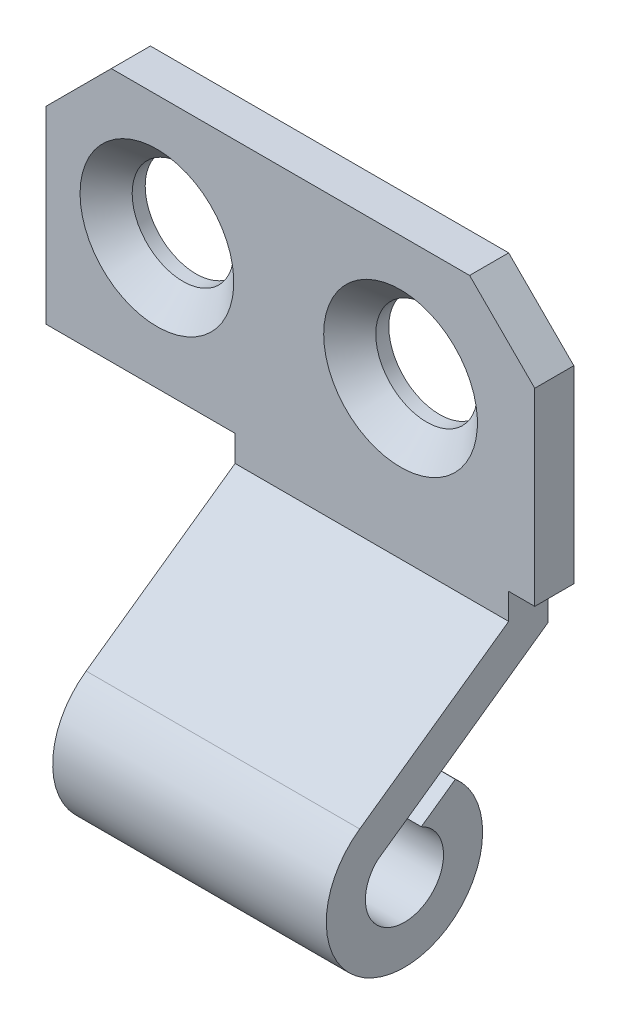
SolidWorks part; units mm, degrees
ref_plane "Płaszczyzna przednia" through (0, 0, 0) normal (0, 0, 1) x (1, 0, 0)
ref_plane "Płaszczyzna górna" through (0, 0, 0) normal (0, 1, 0) x (1, 0, 0)
ref_plane "Płaszczyzna prawa" through (0, 0, 0) normal (1, 0, 0) x (0, 0, -1)
sketch "Szkic1" plane through (0, 0, 0) normal (0, 0, 1) x (1, 0, 0)
  line L0 (-13.75, 9.75) -> (-18.75, 4.75)
  line L1 (-13.75, 9.75) -> (13.75, 9.75)
  line L2 (-18.75, 4.75) -> (-18.75, -9.75)
  line L3 (-18.75, -9.75) -> (-4.25, -9.75)
  line L4 (18.75, 4.75) -> (18.75, -9.75)
  line L5 (-4.25, -9.75) -> (-4.25, -11.75)
  line L6 (13.75, 9.75) -> (18.75, 4.75)
  line L7 (16.75, -9.75) -> (16.75, -11.75)
  line L8 (-4.25, -11.75) -> (16.75, -11.75)
  line L9 (16.75, -9.75) -> (18.75, -9.75)
  circle A0 centre (8.45, 0.25) radius 3.9
  circle A1 centre (-10.25, 0.25) radius 3.9
  dimension "D7" = 7.8
  dimension "D1" = 135
  dimension "D2" = 14.5
  dimension "D3" = 18.75
  dimension "D4" = 9.75
  dimension "D5" = 37.5
  dimension "D6" = 5
  dimension "D8" = 10.3
  dimension "D9" = 9.5
  dimension "D10" = 8.5
  dimension "D12" = 2
  dimension "D13" = 2
  dimension "D11" = 21
extrude "Dodanie-wyciągnięcie1" add sketch "Szkic1" along normal blind 3
chamfer "Sfazowanie1" distance 2 angle 45 2 edges at (-6.35, 0.25, 3) (12.35, 0.25, 3)
sketch "Szkic2" plane through (0, 0, 0) normal (1, 0, 0) x (0, 0, -1)
  line L0 (-3, -11.75) -> (-14.4334, -19.8295)
  line L1 (0, -13.3486) -> (0, -11.75)
  line L2 (0, -11.75) -> (-3, -11.75)
  line L3 (0, -13.3486) -> (-13.0935, -22.6012)
  line L10 (-7.0922, -20.1971) -> (-9.7054, -22.0437)
  arc A0 (-14.4334, -19.8295) -> (-7.0922, -20.1971) centre (-11, -24.75) ccw
  arc A1 (-13.0935, -22.6012) -> (-9.7054, -22.0437) centre (-11, -24.75) ccw
  dimension "D3" = 12
  dimension "D4" = 6
  dimension "D1" = 14
  dimension "D2" = 7.0922
  dimension "D5" = 9.7054
  dimension "D6" = 11
  dimension "D7" = 13.0935
extrude "Dodanie-wyciągnięcie2" add sketch "Szkic2" along normal blind 16.75 and the other way blind 4.25 contours A0 L10 A1 L3 L1 L2 L0
